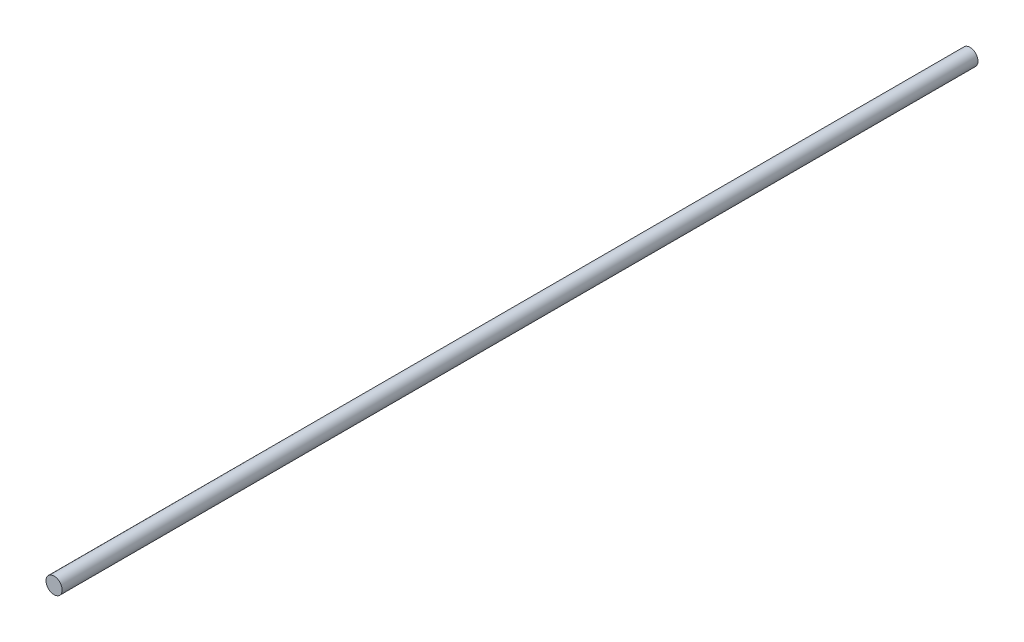
SolidWorks part; units mm, degrees
ref_plane "Front Plane" through (0, 0, 0) normal (0, 0, 1) x (1, 0, 0)
ref_plane "Top Plane" through (0, 0, 0) normal (0, 1, 0) x (1, 0, 0)
ref_plane "Right Plane" through (0, 0, 0) normal (1, 0, 0) x (0, 0, -1)
sketch "Sketch1" plane through (0, 0, 0) normal (0, 0, 1) x (1, 0, 0)
  circle A0 centre (0, 0) radius 6
  point P3 (0, 0)
  dimension "D1" = 12
extrude "Boss-Extrude1" add sketch "Sketch1" along normal blind 680
